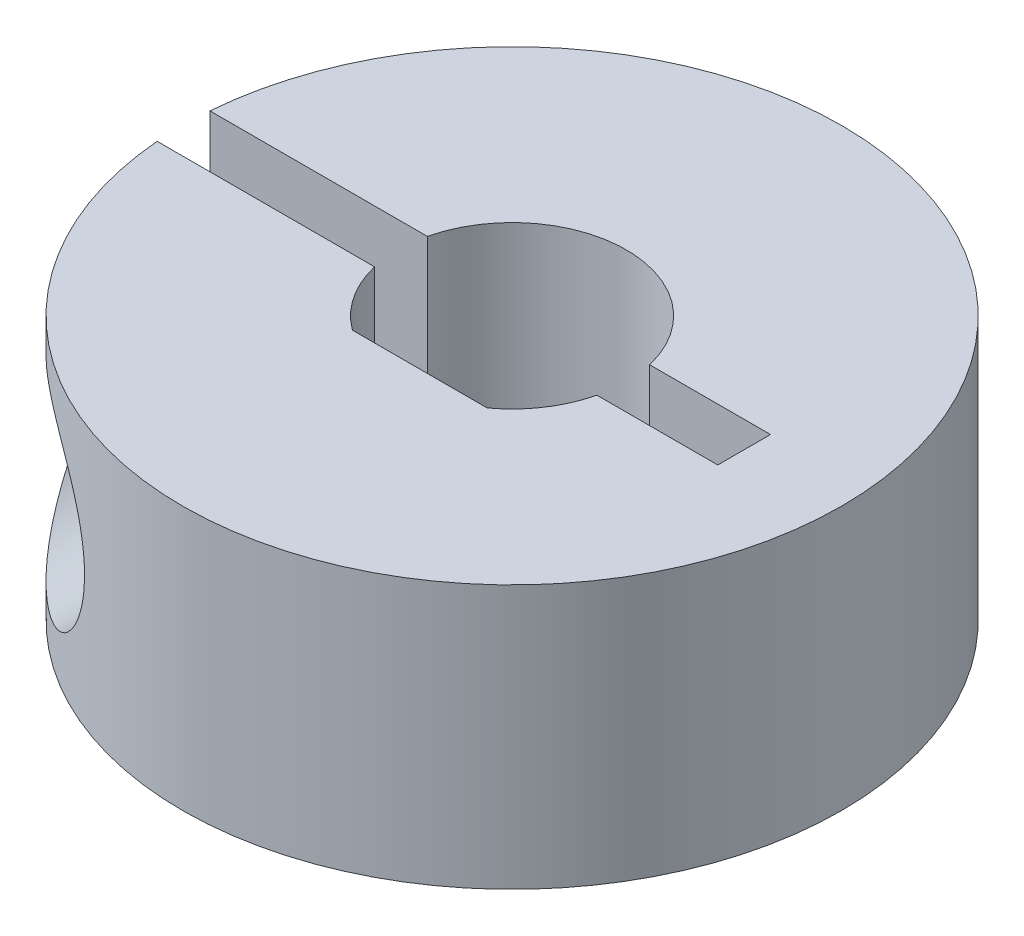
SolidWorks part; units mm, degrees
ref_plane "Front Plane" through (0, 0, 0) normal (0, 0, 1) x (1, 0, 0)
ref_plane "Top Plane" through (0, 0, 0) normal (0, 1, 0) x (1, 0, 0)
ref_plane "Right Plane" through (0, 0, 0) normal (1, 0, 0) x (0, 0, -1)
sketch "Sketch2" plane through (0, 0, 0) normal (0, 1, 0) x (1, 0, 0)
  line L0 (-1.8991, 0) -> (7.5, 0) construction
  line L1 (-7.476, 0.6) -> (-2.5298, 0.6)
  line L2 (2.5298, 0.6) -> (5.2798, 0.6)
  line L3 (5.2798, 0.6) -> (5.2798, -0.6)
  line L4 (5.2798, -0.6) -> (2.5298, -0.6)
  line L5 (-1.533, -2.1) -> (1.533, -2.1)
  line L6 (-2.5298, -0.6) -> (-7.476, -0.6)
  arc A0 (-7.476, -0.6) -> (-7.476, 0.6) centre (0, 0) ccw
  arc A1 (2.5298, 0.6) -> (-2.5298, 0.6) centre (0, 0) ccw
  arc A2 (-2.5298, -0.6) -> (-1.533, -2.1) centre (0, 0) ccw
  arc A3 (1.533, -2.1) -> (2.5298, -0.6) centre (0, 0) ccw
  dimension "D1" = 15
  dimension "D4" = 5.2
  dimension "D2" = 1.2
  dimension "D3" = 0.6
  dimension "D5" = 2.1
  dimension "D6" = 1.2
  dimension "D7" = 2.75
extrude "Boss-Extrude1" add sketch "Sketch2" along normal blind 6
ref_plane "Plane1" through (0, 0, 3) normal (0, 0, 1) x (1, 0, 0)
sketch "Sketch4" plane through (0, 0, 3) normal (0, 0, 1) x (1, 0, 0)
  line L0 (0, -3.3) -> (0, 3.3) construction
  line L1 (0, 8) -> (0, -0.4885) construction
  line L3 (-2.5, 8) -> (-2.5, 0) construction
  line L4 (-7.476, 6) -> (-7.476, 0) construction
  circle A0 centre (-5.1, 3) radius 1.2
  point P10 (-7.476, 3)
  dimension "D4" = 2.4
  dimension "D1" = 2.5
  dimension "D2" = 2.6
extrude "Cut-Extrude1" cut sketch "Sketch4" against normal blind 2
sketch "Sketch5" plane through (0, 0, 3) normal (0, 0, 1) x (1, 0, 0)
  line L1 (-7.476, 6) -> (-7.476, 0) construction
  line L2 (-2.5298, 6) -> (-7.476, 6) construction
  circle A0 centre (-5.0029, 3) radius 2.25
  point P7 (-7.476, 3)
  point P11 (-5.0029, 6)
  dimension "D1" = 4.5
extrude "Cut-Extrude2" cut sketch "Sketch5" along normal through all
sketch "Sketch7" plane through (0, 0, -0.6) normal (0, 0, 1) x (1, 0, 0)
  line L0 (-7.476, 6) -> (-7.476, 0) construction
  point P0 (-5.1, 3)
  point P5 (-7.476, 3)
sketch "Sketch9" plane through (0, 0, 0) normal (0, 0, 1) x (1, 0, 0)
  circle A0 centre (-5.1, 3) radius 1.085
  dimension "D1" = 2.17
extrude "Cut-Extrude3" cut sketch "Sketch9" against normal blind 10
hole_wizard "#2-56 Tapped Hole1" positions "3DSketch2" profile "Sketch8" tap size "#2-56" standard "ANSI Inch"
sketch3d "3DSketch2"
  point P0 (-5.275, 3, -0.6)
sketch "Sketch8" plane through (-5.275, 3, -0.6) normal (1, 0, 0) x (0, -1, 0)
  line L0 (0, 0) -> (0, 7.4)
  line L1 (0, 7.4) -> (0.889, 7.4)
  line L2 (0.889, 7.4) -> (0.889, 0)
  line L5 (0.889, 0) -> (0, 0)
  line L11 (0, -6.35) -> (0, 107.95) construction
  dimension "Thru Tap Drill Dia." = 1.778
  dimension "Thru Tap Drill Depth" = 7.4
